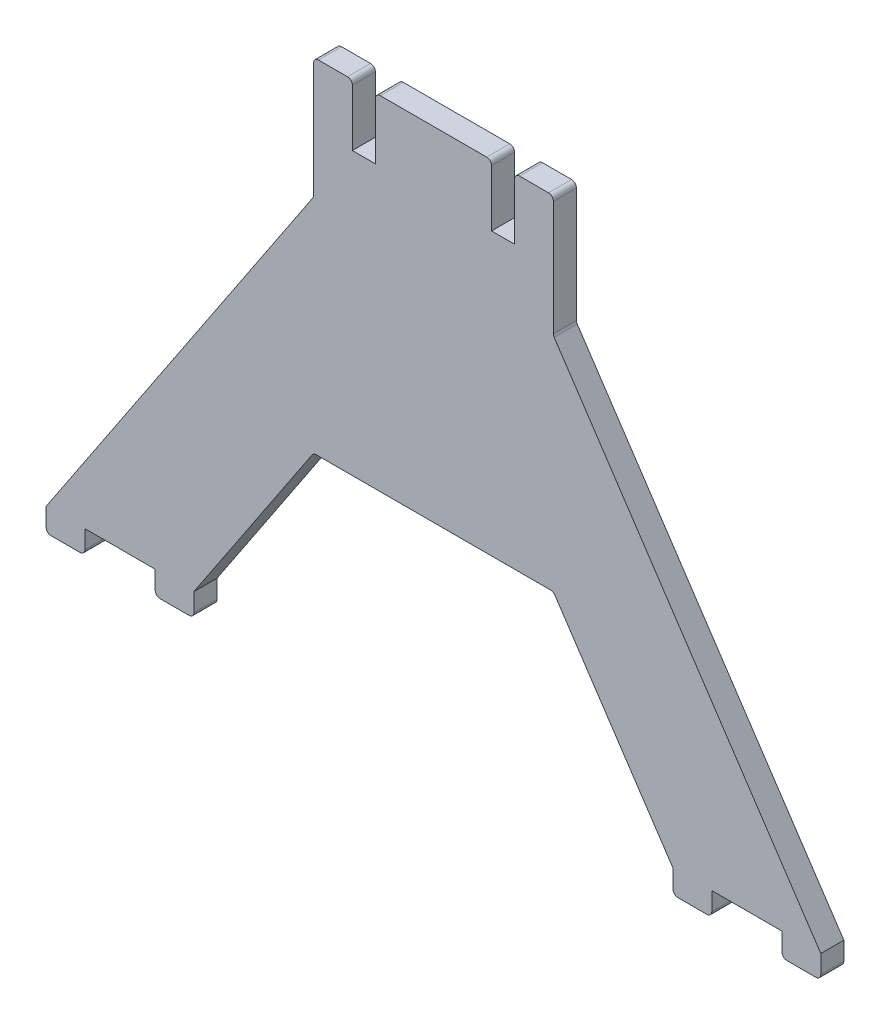
SolidWorks part; units mm, degrees
material "Mahogany"
ref_plane "Front Plane" through (0, 0, 0) normal (0, 0, 1) x (1, 0, 0)
ref_plane "Top Plane" through (0, 0, 0) normal (0, 1, 0) x (1, 0, 0)
ref_plane "Right Plane" through (0, 0, 0) normal (1, 0, 0) x (0, 0, -1)
sketch "Sketch2" plane through (0, 0, 0) normal (0, 0, 1) x (1, 0, 0)
  line L0 (-23, -45.0481) -> (-1, -45.0481)
  line L1 (-35.7625, -45.0481) -> (-29.7625, -45.0481)
  line L2 (-36.7625, -46.0481) -> (-36.7625, -69.7656)
  line L3 (-24, -70.0681) -> (0, -70.0681) construction
  line L4 (4.7625, -57.7481) -> (0, -57.7481)
  line L5 (45.4816, -153) -> (60, -153)
  line L6 (45.4816, -153) -> (45.4816, -156.7625)
  line L7 (38.4816, -157.7625) -> (44.4816, -157.7625)
  line L8 (0, -57.7481) -> (0, -70.0681)
  line L9 (0, -70.0681) -> (4.7625, -70.0681)
  line L10 (4.7625, -70.0681) -> (4.7625, -57.7481)
  line L11 (4.7625, -57.7481) -> (0, -57.7481)
  line L12 (-28.7625, -57.7481) -> (-28.7625, -70.0681)
  line L13 (-28.7625, -70.0681) -> (-24, -70.0681)
  line L14 (-24, -70.0681) -> (-24, -57.7481)
  line L15 (-24, -57.7481) -> (-28.7625, -57.7481)
  line L16 (-28.7625, -57.7481) -> (-28.7625, -70.0681) construction
  line L17 (-28.7625, -70.0681) -> (-24, -70.0681)
  line L18 (-24, -70.0681) -> (-24, -57.7481) construction
  line L19 (-24, -57.7481) -> (-28.7625, -57.7481) construction
  line L20 (0, -57.7481) -> (0, -70.0681) construction
  line L21 (-28.7625, -57.7481) -> (-24, -57.7481)
  line L22 (-28.7625, -57.7481) -> (-28.7625, -46.0481)
  line L23 (0, -70.0681) -> (4.7625, -70.0681)
  line L24 (-24, -57.7481) -> (-24, -46.0481)
  line L25 (4.7625, -70.0681) -> (4.7625, -57.7481) construction
  line L26 (4.7625, -57.7481) -> (0, -57.7481) construction
  line L27 (-24, -153) -> (-28.7625, -153) construction
  line L28 (37.4816, -153) -> (37.4816, -156.7625)
  line L29 (-24, -157.7625) -> (-28.7625, -157.7625) construction
  line L30 (-24, -153) -> (-28.7625, -153) construction
  line L31 (-24, -157.7625) -> (-28.7625, -157.7625) construction
  line L32 (-80.7773, -153) -> (73.6528, -153) construction
  line L33 (-47.921, -157.7625) -> (106.5092, -157.7625) construction
  line L34 (-36.9302, -70.3199) -> (-92, -153)
  line L35 (-12, -45.0481) -> (-12, -157.7625) construction
  line L36 (-61.4816, -153) -> (-37.0593, -116.3332)
  line L37 (-36.227, -115.8876) -> (12.227, -115.8876)
  line L38 (60, -153) -> (60, -156.7625)
  line L39 (67, -157.7625) -> (61, -157.7625)
  line L40 (-92, -153) -> (-92, -156.7625)
  line L41 (-91, -157.7625) -> (-85, -157.7625)
  line L42 (-84, -153) -> (-84, -156.7625)
  line L43 (68, -153) -> (68, -156.7625)
  line L44 (-61.4816, -153) -> (-61.4816, -156.7625)
  line L45 (-62.4816, -157.7625) -> (-68.4816, -157.7625)
  line L46 (-69.4816, -153) -> (-69.4816, -156.7625)
  line L47 (37.4816, -153) -> (13.0593, -116.3332)
  line L48 (12.9302, -70.3199) -> (68, -153)
  line L49 (0, -57.7481) -> (0, -46.0481)
  line L50 (4.7625, -57.7481) -> (4.7625, -46.0481)
  line L51 (12.7625, -46.0481) -> (12.7625, -69.7656)
  line L52 (11.7625, -45.0481) -> (5.7625, -45.0481)
  line L54 (-69.4816, -153) -> (-84, -153)
  arc A0 (-84, -156.7625) -> (-85, -157.7625) centre (-85, -156.7625) cw
  arc A1 (-69.4816, -156.7625) -> (-68.4816, -157.7625) centre (-68.4816, -156.7625) ccw
  arc A2 (-61.4816, -156.7625) -> (-62.4816, -157.7625) centre (-62.4816, -156.7625) cw
  arc A3 (-91, -157.7625) -> (-92, -156.7625) centre (-91, -156.7625) cw
  arc A4 (-36.227, -115.8876) -> (-37.0593, -116.3332) centre (-36.227, -116.8876) ccw
  arc A5 (-23, -45.0481) -> (-24, -46.0481) centre (-23, -46.0481) ccw
  arc A6 (-29.7625, -45.0481) -> (-28.7625, -46.0481) centre (-29.7625, -46.0481) cw
  arc A7 (-35.7625, -45.0481) -> (-36.7625, -46.0481) centre (-35.7625, -46.0481) ccw
  arc A8 (-36.7625, -69.7656) -> (-36.9302, -70.3199) centre (-37.7625, -69.7656) cw
  arc A9 (12.7625, -69.7656) -> (12.9302, -70.3199) centre (13.7625, -69.7656) ccw
  arc A10 (11.7625, -45.0481) -> (12.7625, -46.0481) centre (11.7625, -46.0481) cw
  arc A11 (5.7625, -45.0481) -> (4.7625, -46.0481) centre (5.7625, -46.0481) ccw
  arc A12 (-1, -45.0481) -> (0, -46.0481) centre (-1, -46.0481) cw
  arc A13 (12.227, -115.8876) -> (13.0593, -116.3332) centre (12.227, -116.8876) cw
  arc A14 (67, -157.7625) -> (68, -156.7625) centre (67, -156.7625) ccw
  arc A15 (37.4816, -156.7625) -> (38.4816, -157.7625) centre (38.4816, -156.7625) ccw
  arc A16 (45.4816, -156.7625) -> (44.4816, -157.7625) centre (44.4816, -156.7625) cw
  arc A17 (60, -156.7625) -> (61, -157.7625) centre (61, -156.7625) ccw
  point P3 (-12, -70.0681)
  point P17 (-84, -157.7625)
  point P32 (12.7625, -70.0681)
  point P39 (-69.4816, -157.7625)
  point P42 (-61.4816, -157.7625)
  point P45 (-92, -157.7625)
  point P48 (-36.7625, -115.8876)
  point P51 (-24, -45.0481)
  point P58 (-36.7625, -70.0681)
  point P90 (-12, -115.8876)
  point P91 (0, -45.0481)
  point P92 (12.7625, -115.8876)
  point P93 (68, -157.7625)
  point P94 (37.4816, -157.7625)
  point P95 (45.4816, -157.7625)
  point P96 (60, -157.7625)
  dimension "D4" = 1
  dimension "D1" = 0
  dimension "D2" = 0
  dimension "D3" = 12.7
  dimension "D5" = 8
  dimension "D6" = 80
  dimension "D7" = 25.4
  dimension "D8" = 8
  dimension "D9" = 8
extrude "Boss-Extrude1" add sketch "Sketch2" along normal blind 4.7625 contours L34 L40 A3 L41 A0 L42 L54 L46 A1 L45 A2 L44 L36 A4 L37 A13 L47 L28 A15 L7 A16 L6 L5 L38 A17 L39 A14 L43 L48 A9 L51 A10 L52 A11 L50 L4 L49 A12 L0 A5 L24 L21 L22 A6 L1 A7 L2 A8
